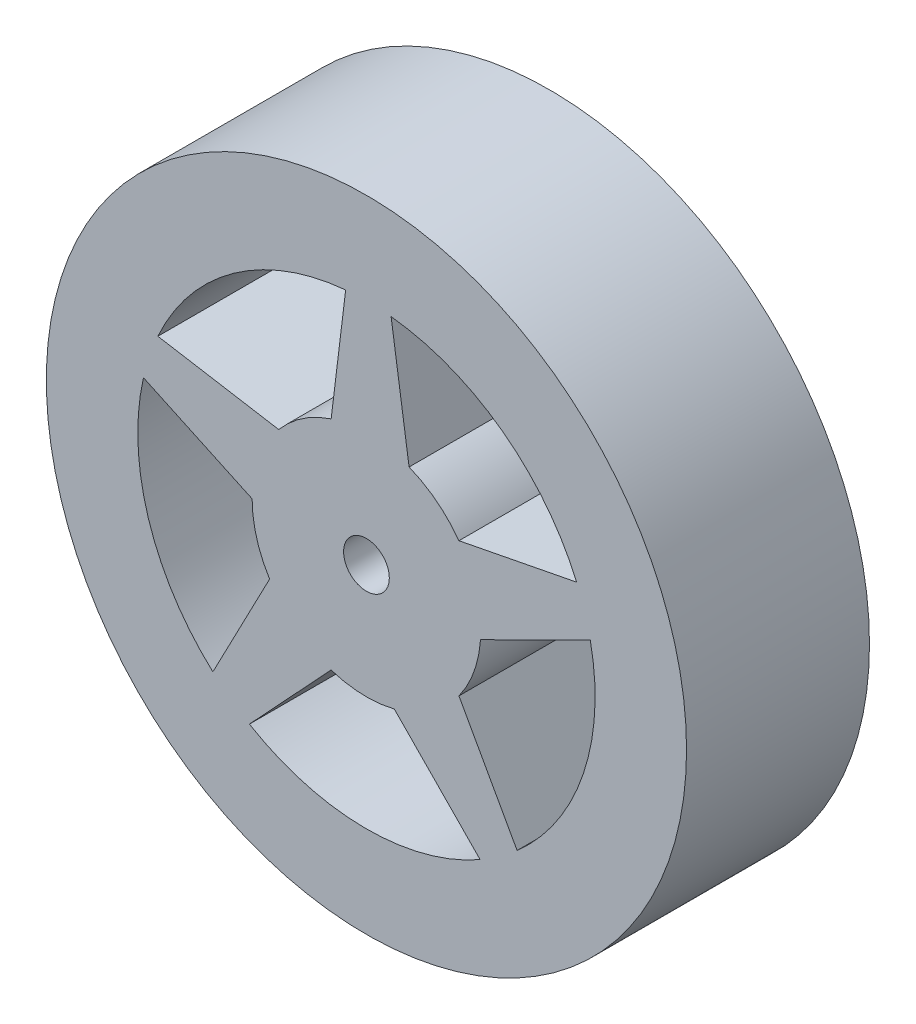
SolidWorks part; units mm, degrees
ref_plane "前视基准面" through (0, 0, 0) normal (0, 0, 1) x (1, 0, 0)
ref_plane "上视基准面" through (0, 0, 0) normal (0, 1, 0) x (1, 0, 0)
ref_plane "右视基准面" through (0, 0, 0) normal (1, 0, 0) x (0, 0, -1)
sketch "草图1" plane through (0, 0, 0) normal (0, 0, 1) x (1, 0, 0)
  circle A0 centre (0, 0) radius 35
  circle A1 centre (0, 0) radius 25
  dimension "D1" = 70
  dimension "D2" = 50
extrude "凸台-拉伸1" add sketch "草图1" along normal mid plane 20
sketch "草图2" plane through (0, 0, 0) normal (0, 0, 1) x (1, 0, 0)
  line L0 (-3.8594, 11.8893) -> (-1.4388, 31.7128)
  line L1 (-1.4388, 31.7128) -> (1.6786, 31.7128)
  line L2 (1.6786, 31.7128) -> (4.6625, 11.5979)
  circle A0 centre (0, 0) radius 12.5
  dimension "D1" = 25
extrude "凸台-拉伸2" add sketch "草图2" along normal mid plane 20 contours A0 | A0 L2 L1 L0
pattern_circular "阵列(圆周)1" count 5 over 360 about axis through (0, 0, 0) along (0, 0, 1) of "凸台-拉伸2"
sketch "草图3" plane through (0, 0, 10) normal (0, 0, 1) x (1, 0, 0)
  circle A0 centre (0, 0) radius 2.5
  dimension "D1" = 5
extrude "切除-拉伸1" cut sketch "草图3" against normal through all
sketch "草图4" plane through (0, 0, -10) normal (0, 0, -1) x (-1, 0, 0)
  line L1 (0, 8) -> (-6.9282, 4)
  line L2 (-6.9282, 4) -> (-6.9282, -4)
  line L3 (-6.9282, -4) -> (0, -8)
  line L4 (0, -8) -> (6.9282, -4)
  line L5 (6.9282, -4) -> (6.9282, 4)
  line L6 (6.9282, 4) -> (0, 8)
  circle A0 centre (0, 0) radius 6.9282 construction
  dimension "D1" = 8
extrude "切除-拉伸2" cut sketch "草图4" against normal blind 10
